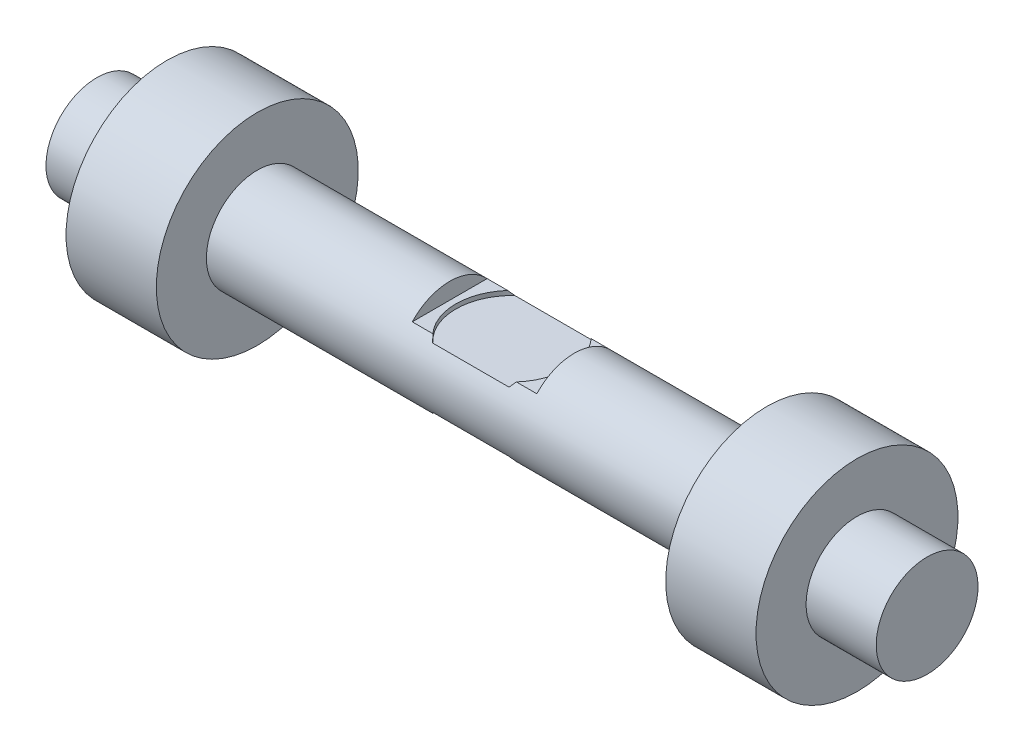
SolidWorks part; units mm, degrees
ref_plane "Front Plane" through (0, 0, 0) normal (0, 0, 1) x (1, 0, 0)
ref_plane "Top Plane" through (0, 0, 0) normal (0, 1, 0) x (1, 0, 0)
ref_plane "Right Plane" through (0, 0, 0) normal (1, 0, 0) x (0, 0, -1)
sketch "Sketch1" plane through (0, 0, 0) normal (0, 0, 1) x (1, 0, 0)
  line L0 (0, 0) -> (1928.3266, 0) construction
  line L1 (0, 0) -> (0, 113.4144)
  line L2 (0, 113.4144) -> (156.3014, 113.4144)
  line L3 (156.3014, 113.4144) -> (156.3014, 225)
  line L4 (156.3014, 225) -> (357.4475, 225)
  line L5 (357.4475, 225) -> (357.4475, 113.4144)
  line L6 (357.4475, 113.4144) -> (1492.5525, 113.4144)
  line L7 (1492.5525, 113.4144) -> (1492.5525, 225)
  line L8 (1492.5525, 225) -> (1693.6986, 225)
  line L9 (1693.6986, 225) -> (1693.6986, 113.4144)
  line L10 (1693.6986, 113.4144) -> (1850, 113.4144)
  line L11 (1850, 113.4144) -> (1850, 0)
  line L12 (925, 113.4144) -> (925, -371.4646) construction
  line L13 (0, 0) -> (1850, 0)
  dimension "D1" = 1850
  dimension "D2" = 225
  dimension "D3" = 201.146
revolve "Revolve1" add sketch "Sketch1" angle 360 about L13
ref_plane "Plane1" through (0, 0, 120) normal (0, 0, 1) x (1, 0, 0)
sketch "Sketch2" plane through (0, 0, 120) normal (0, 0, 1) x (1, 0, 0)
  line L0 (0, 0) -> (1900.5102, 0) construction
  line L1 (1492.5525, 113.4144) -> (357.4475, 113.4144) construction
  line L2 (1063.7755, 76.8288) -> (786.2245, 76.8288)
  line L3 (1063.7755, 76.8288) -> (1063.7755, 150)
  line L4 (1063.7755, 150) -> (786.2245, 150)
  line L5 (786.2245, 76.8288) -> (786.2245, 150)
  line L6 (1063.7755, 76.8288) -> (786.2245, 150) construction
  line L7 (1063.7755, 150) -> (786.2245, 76.8288) construction
  line L8 (1063.7755, -150) -> (786.2245, -76.8288) construction
  line L9 (1063.7755, -76.8288) -> (786.2245, -150) construction
  line L10 (786.2245, -76.8288) -> (786.2245, -150)
  line L11 (1063.7755, -150) -> (786.2245, -150)
  line L12 (1063.7755, -76.8288) -> (1063.7755, -150)
  line L13 (1063.7755, -76.8288) -> (786.2245, -76.8288)
  point P3 (925, 113.4144)
  point P14 (925, -113.4144)
extrude "Cut-Extrude1" cut sketch "Sketch2" against normal through all
sketch "Sketch3" plane through (0, 76.8288, 0) normal (0, 1, 0) x (1, 0, 0)
  circle A0 centre (925, 0) radius 125
  dimension "D1" = 250
extrude "Cut-Extrude2" cut sketch "Sketch3" against normal blind 10
mirror "Mirror1" about plane through (0, 0, 0) normal (0, 1, 0) of "Cut-Extrude2"
